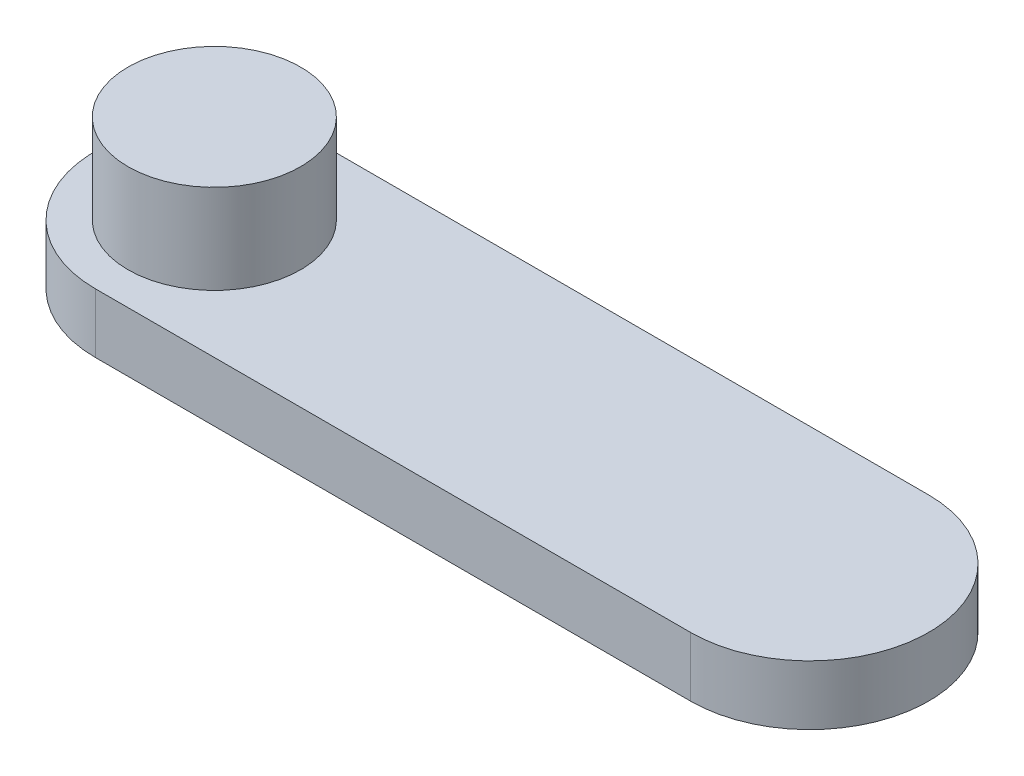
SolidWorks part; units mm, degrees
ref_plane "Front Plane" through (0, 0, 0) normal (0, 0, 1) x (1, 0, 0)
ref_plane "Top Plane" through (0, 0, 0) normal (0, 1, 0) x (1, 0, 0)
ref_plane "Right Plane" through (0, 0, 0) normal (1, 0, 0) x (0, 0, -1)
sketch "Sketch1" plane through (0, 0, 0) normal (0, 1, 0) x (1, 0, 0)
  line L0 (-45.7402, 0) -> (54.2598, 0) construction
  line L1 (-45.7402, 20) -> (54.2598, 20)
  line L2 (-45.7402, -20) -> (54.2598, -20)
  arc A0 (-45.7402, 20) -> (-45.7402, -20) centre (-45.7402, 0) ccw
  arc A1 (54.2598, -20) -> (54.2598, 20) centre (54.2598, 0) ccw
  point P3 (4.2598, 0)
  dimension "D2" = 100
  dimension "D3" = 40
extrude "Boss-Extrude2" add sketch "Sketch1" along normal blind 10
sketch "Sketch2" plane through (0, 10, 0) normal (0, 1, 0) x (1, 0, 0)
  circle A0 centre (-45.7402, 0) radius 14.5
extrude "Boss-Extrude3" add sketch "Sketch2" along normal blind 15
